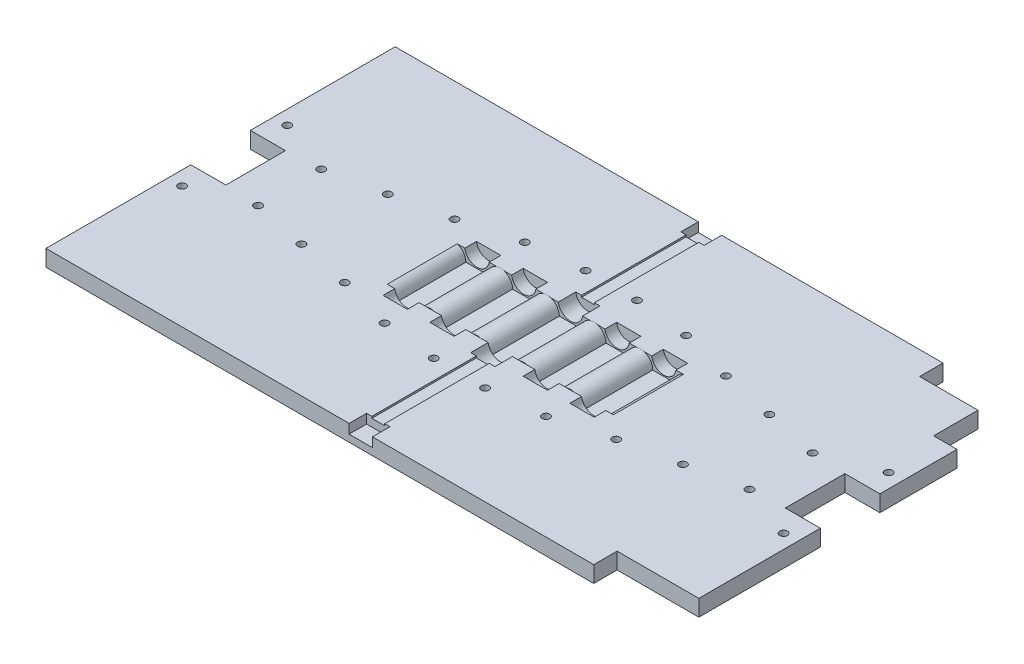
SolidWorks part; units mm, degrees
ref_plane "Front Plane" through (0, 0, 0) normal (0, 0, 1) x (1, 0, 0)
ref_plane "Top Plane" through (0, 0, 0) normal (0, 1, 0) x (1, 0, 0)
ref_plane "Right Plane" through (0, 0, 0) normal (1, 0, 0) x (0, 0, -1)
sketch "Sketch1" plane through (0, 0, 0) normal (0, 1, 0) x (1, 0, 0)
  line L1 (269.5, -149.5) -> (-269.5, -149.5)
  line L2 (269.5, -149.5) -> (269.5, 149.5)
  line L3 (269.5, 149.5) -> (-269.5, 149.5)
  line L4 (-269.5, -149.5) -> (-269.5, 149.5)
  line L5 (269.5, -149.5) -> (-269.5, 149.5) construction
  line L6 (269.5, 149.5) -> (-269.5, -149.5) construction
  point P0 (0, 0)
  dimension "D1" = 299
  dimension "D2" = 539
extrude "Boss-Extrude1" add sketch "Sketch1" against normal blind 14
sketch "Sketch15" plane through (0, 0, 0) normal (0, 1, 0) x (1, 0, 0)
  line L0 (269.5, 149.5) -> (199.5, 149.5)
  line L1 (269.5, 149.5) -> (-269.5, 149.5) construction
  line L2 (199.5, 149.5) -> (199.5, 129.5)
  line L3 (199.5, 129.5) -> (249.5, 129.5)
  line L4 (249.5, 129.5) -> (249.5, 91.5)
  line L5 (249.5, 91.5) -> (269.5, 91.5)
  line L6 (269.5, -149.5) -> (269.5, 149.5) construction
  line L7 (269.5, 91.5) -> (269.5, 149.5)
  line L8 (269.5, -149.5) -> (199.5, -149.5)
  line L9 (-269.5, -149.5) -> (269.5, -149.5) construction
  line L10 (199.5, -149.5) -> (199.5, -129.5)
  line L11 (199.5, -129.5) -> (269.5, -129.5)
  line L12 (269.5, -129.5) -> (269.5, -149.5)
  dimension "D1" = 20
  dimension "D2" = 20
  dimension "D3" = 20
  dimension "D4" = 70
  dimension "D5" = 70
  dimension "D6" = 58
extrude "Cut-Extrude8" cut sketch "Sketch15" against normal through all
sketch "Sketch2" plane through (0, 0, 0) normal (0, 1, 0) x (1, 0, 0)
  line L0 (-269.5, 0) -> (269.5, 0) construction
  line L1 (-269.5, 149.5) -> (-269.5, -149.5) construction
  line L4 (-269.5, -25.5) -> (-239.5, -25.5)
  line L5 (-269.5, -25.5) -> (-269.5, 25.5)
  line L6 (-269.5, 25.5) -> (-239.5, 25.5)
  line L7 (-239.5, -25.5) -> (-239.5, 25.5)
  point P10 (-269.5, 0)
  dimension "D1" = 51
  dimension "D2" = 30
extrude "Cut-Extrude1" cut sketch "Sketch2" against normal through all
mirror "Mirror1" about plane through (0, 0, 0) normal (1, 0, 0) of "Cut-Extrude1"
sketch "Sketch8" plane through (0, -14, 0) normal (0, -1, 0) x (1, 0, 0)
  point P0 (-255, 105)
  point P1 (-170, 105)
  point P5 (-85, 105)
  point P6 (0, 105)
  point P7 (85, 105)
  point P8 (170, 105)
  point P9 (255, 105)
  point P10 (-170, 35)
  point P11 (-85, 35)
  point P12 (0, 35)
  point P13 (85, 35)
  point P14 (170, 35)
  point P15 (255, 35)
  point P16 (-170, -35)
  point P17 (-85, -35)
  point P18 (0, -35)
  point P19 (85, -35)
  point P20 (170, -35)
  point P21 (255, -35)
  point P22 (-170, -105)
  point P23 (-85, -105)
  point P24 (0, -105)
  point P25 (85, -105)
  point P26 (170, -105)
  point P27 (255, -105)
  point P28 (-255, 35)
  point P29 (-255, -35)
  point P30 (-255, -105)
  dimension "D1" = 255
  dimension "D2" = 105
  dimension "D3" = 7
  dimension "D4" = 4
sketch "Sketch16" plane through (0, 0, 0) normal (0, 1, 0) x (1, 0, 0)
  line L1 (100, -30) -> (-100, -30)
  line L2 (100, -30) -> (100, 30)
  line L3 (100, 30) -> (-100, 30)
  line L4 (-100, -30) -> (-100, 30)
  line L5 (100, -30) -> (-100, 30) construction
  line L6 (100, 30) -> (-100, -30) construction
  point P0 (0, 0)
  dimension "D1" = 200
  dimension "D2" = 60
extrude "Cut-Extrude9" cut sketch "Sketch16" against normal blind 10
sketch "Sketch17" plane through (0, 0, -30) normal (0, 0, 1) x (1, 0, 0)
  circle A0 centre (0, 1.5) radius 10.5
  dimension "D1" = 21
  dimension "D2" = 1.5
extrude "Cut-Extrude10" cut sketch "Sketch17" against normal blind 15
sketch "Sketch18" plane through (0, 0, -30) normal (0, 0, 1) x (1, 0, 0)
  line L2 (-79.9719, 1.5) -> (-39.9719, 1.5) construction
  line L3 (-10.3923, 0) -> (-100, 0) construction
  circle A0 centre (-39.9719, 1.5) radius 10.5
  circle A1 centre (-79.9719, 1.5) radius 10.5
  dimension "D1" = 21
  dimension "D2" = 40
  dimension "D3" = 40
  dimension "D4" = 1.5
extrude "Cut-Extrude11" cut sketch "Sketch18" against normal blind 10
sketch "Sketch19" plane through (0, 0, -30) normal (0, 0, 1) x (1, 0, 0)
  line L0 (100, -10) -> (-100, -10) construction
  line L1 (-9.5, -10) -> (-30.5, -10)
  line L3 (-89.5, -10) -> (-100, -10)
  line L4 (-49.5, -10) -> (-70.5, -10)
  line L5 (-100, -10) -> (-100, 0)
  line L6 (-100, 0) -> (-96.7984, 0)
  line L7 (-269.5, 0) -> (199.5, 0) construction
  arc A0 (-49.5, -10) -> (-70.5, -10) centre (-60, -10) ccw
  arc A1 (-9.5, -10) -> (-30.5, -10) centre (-20, -10) ccw
  arc A2 (-89.5, -10) -> (-96.7984, 0) centre (-100, -10) ccw
  dimension "D3" = 21
  dimension "D1" = 40
  dimension "D2" = 40
  dimension "D4" = 20
  dimension "D5" = 10
extrude "Boss-Extrude2" add sketch "Sketch19" along normal up to surface (60 mm away) up to face at (0, -5, 30)
mirror "Mirror2" about plane through (0, 0, 0) normal (1, 0, 0) of "Boss-Extrude2"
mirror "Mirror3" about plane through (0, 0, 0) normal (1, 0, 0) of "Cut-Extrude11"
mirror "Mirror4" about plane through (0, 0, 0) normal (0, 0, 1) of "Cut-Extrude10", "Mirror3", "Cut-Extrude11"
sketch "Sketch20" plane through (0, 0, 0) normal (0, 1, 0) x (1, 0, 0)
  line L0 (-227.025, 3) -> (-227.025, -3)
  line L50 (-90.5, -40) -> (-69.5, -40)
  line L51 (-90.5, -30) -> (-90.5, -40)
  line L52 (-100, -30) -> (-90.5, -30)
  line L53 (-227.025, -3) -> (-100, -30)
  line L54 (-260, -3) -> (-227.025, -3)
  line L55 (-227.025, 3) -> (-260, 3)
  line L56 (-100, 30) -> (-227.025, 3)
  line L57 (-90.5, 30) -> (-100, 30)
  line L58 (-90.5, 40) -> (-90.5, 30)
  line L59 (-69.5, 40) -> (-90.5, 40)
  line L60 (-69.5, 30) -> (-69.5, 40)
  line L61 (-50.5, 30) -> (-69.5, 30)
  line L62 (-50.5, 40) -> (-50.5, 30)
  line L63 (-29.5, 40) -> (-50.5, 40)
  line L64 (-29.5, 30) -> (-29.5, 40)
  line L65 (-10.5, 30) -> (-29.5, 30)
  line L66 (-10.5, 45) -> (-10.5, 30)
  line L67 (10.5, 45) -> (-10.5, 45)
  line L68 (10.5, 30) -> (10.5, 45)
  line L69 (29.5, 30) -> (10.5, 30)
  line L70 (29.5, 40) -> (29.5, 30)
  line L71 (50.5, 40) -> (29.5, 40)
  line L72 (50.5, 30) -> (50.5, 40)
  line L73 (69.5, 30) -> (50.5, 30)
  line L74 (69.5, 40) -> (69.5, 30)
  line L75 (90.5, 40) -> (69.5, 40)
  line L76 (90.5, 30) -> (90.5, 40)
  line L77 (100, 30) -> (90.5, 30)
  line L78 (90.5, -30) -> (100, -30)
  line L79 (260, 3) -> (227.025, 3)
  line L80 (90.5, -30) -> (100, -30)
  line L81 (100, -30) -> (227.025, -3)
  line L82 (100, -30) -> (227.025, -3)
  line L83 (90.5, -40) -> (90.5, -30)
  line L84 (69.5, -40) -> (90.5, -40)
  line L85 (69.5, -30) -> (69.5, -40)
  line L86 (50.5, -30) -> (69.5, -30)
  line L87 (50.5, -40) -> (50.5, -30)
  line L88 (29.5, -40) -> (50.5, -40)
  line L89 (29.5, -30) -> (29.5, -40)
  line L90 (10.5, -30) -> (29.5, -30)
  line L91 (10.5, -45) -> (10.5, -30)
  line L92 (-10.5, -45) -> (10.5, -45)
  line L93 (-10.5, -30) -> (-10.5, -45)
  line L94 (-29.5, -30) -> (-10.5, -30)
  line L95 (-29.5, -40) -> (-29.5, -30)
  line L96 (-50.5, -40) -> (-29.5, -40)
  line L97 (-50.5, -30) -> (-50.5, -40)
  line L98 (-69.5, -30) -> (-50.5, -30)
  line L99 (-69.5, -40) -> (-69.5, -30)
  line L100 (-90.5, -40) -> (-69.5, -40)
  line L101 (-90.5, -30) -> (-90.5, -40)
  line L102 (-100, -30) -> (-90.5, -30)
  line L103 (-227.025, -3) -> (-100, -30)
  line L104 (-260, -3) -> (-227.025, -3)
  line L105 (-227.025, 3) -> (-260, 3)
  line L106 (-100, 30) -> (-227.025, 3)
  line L107 (-90.5, 30) -> (-100, 30)
  line L108 (-90.5, 40) -> (-90.5, 30)
  line L109 (-69.5, 40) -> (-90.5, 40)
  line L110 (-69.5, 30) -> (-69.5, 40)
  line L111 (-50.5, 30) -> (-69.5, 30)
  line L112 (-50.5, 40) -> (-50.5, 30)
  line L113 (-29.5, 40) -> (-50.5, 40)
  line L114 (-29.5, 30) -> (-29.5, 40)
  line L115 (-10.5, 30) -> (-29.5, 30)
  line L116 (-10.5, 45) -> (-10.5, 30)
  line L117 (10.5, 45) -> (-10.5, 45)
  line L118 (10.5, 30) -> (10.5, 45)
  line L119 (29.5, 30) -> (10.5, 30)
  line L120 (29.5, 40) -> (29.5, 30)
  line L121 (50.5, 40) -> (29.5, 40)
  line L122 (50.5, 30) -> (50.5, 40)
  line L123 (69.5, 30) -> (50.5, 30)
  line L124 (69.5, 40) -> (69.5, 30)
  line L125 (90.5, 40) -> (69.5, 40)
  line L126 (90.5, 30) -> (90.5, 40)
  line L127 (100, 30) -> (90.5, 30)
  line L129 (260, 3) -> (227.025, 3)
  line L133 (90.5, -40) -> (90.5, -30)
  line L134 (69.5, -40) -> (90.5, -40)
  line L135 (69.5, -30) -> (69.5, -40)
  line L136 (50.5, -30) -> (69.5, -30)
  line L137 (50.5, -40) -> (50.5, -30)
  line L138 (29.5, -40) -> (50.5, -40)
  line L139 (29.5, -30) -> (29.5, -40)
  line L140 (10.5, -30) -> (29.5, -30)
  line L141 (10.5, -45) -> (10.5, -30)
  line L142 (-10.5, -45) -> (10.5, -45)
  line L143 (-10.5, -30) -> (-10.5, -45)
  line L144 (-29.5, -30) -> (-10.5, -30)
  line L145 (-29.5, -40) -> (-29.5, -30)
  line L146 (-50.5, -40) -> (-29.5, -40)
  line L147 (-50.5, -30) -> (-50.5, -40)
  line L148 (-69.5, -30) -> (-50.5, -30)
  line L149 (-69.5, -40) -> (-69.5, -30)
  line L351 (227.025, -3) -> (260, -3)
  line L352 (227.025, -3) -> (260, -3)
  line L353 (227.025, 3) -> (100, 30)
  line L354 (227.025, 3) -> (100, 30)
  arc A2 (-260, 3) -> (-260, -3) centre (-260, 0) ccw
  arc A3 (260, -3) -> (260, 3) centre (260, 0) ccw
  arc A4 (-260, 3) -> (-260, -3) centre (-260, 0) ccw
  arc A5 (260, -3) -> (260, 3) centre (260, 0) ccw
  dimension "D1" = 0
sketch "Sketch22" plane through (0, 0, 0) normal (0, 1, 0) x (1, 0, 0)
  circle A1 centre (-69.1, -60) radius 2.5
  circle A2 centre (-69.1, -60) radius 2.5
  circle A3 centre (-116.2, -47.0034) radius 2.5
  circle A4 centre (-116.2, -47.0034) radius 2.5
  circle A5 centre (-163.3, -36.992) radius 2.5
  circle A6 centre (-163.3, -36.992) radius 2.5
  circle A7 centre (-210.4, -26.9806) radius 2.5
  circle A8 centre (-210.4, -26.9806) radius 2.5
  circle A9 centre (-257.5, -45) radius 2.5
  circle A10 centre (-257.5, -45) radius 2.5
  circle A11 centre (-22, -65) radius 2.5
  circle A12 centre (-22, -65) radius 2.5
  dimension "D1" = 0
  dimension "D2" = 0
  dimension "D3" = 0
  dimension "D4" = 0
  dimension "D5" = 0
  dimension "D6" = 0
hole_wizard "M6 Clearance Hole1" positions "3DSketch1" profile "Sketch9" hole size "M6" standard "ANSI Metric" end condition through all
sketch3d "3DSketch1"
  point P84 (-257.5, 0, 45)
  point P87 (-210.4, 0, 26.9806)
  point P90 (-163.3, 0, 36.992)
  point P93 (-116.2, 0, 47.0034)
  point P96 (-69.1, 0, 60)
  point P99 (-22, 0, 65)
sketch "Sketch9" plane through (-257.5, 0, 45) normal (1, 0, 0) x (0, 0, 1)
  line L0 (0, 0) -> (0, 14)
  line L1 (0, 14) -> (3.3, 14)
  line L2 (3.3, 14) -> (3.3, 0)
  line L5 (3.3, 0) -> (0, 0)
  line L11 (0, -6.35) -> (0, 107.95) construction
  dimension "Thru Hole Dia." = 6.6
  dimension "Thru Hole Depth" = 14
mirror "Mirror6" about plane through (0, 0, 0) normal (1, 0, 0) of "M6 Clearance Hole1"
mirror "Mirror7" about plane through (0, 0, 0) normal (0, 0, 1) of "Mirror6", "M6 Clearance Hole1"
sketch "Sketch23" plane through (0, 0, 0) normal (0, 1, 0) x (1, 0, 0)
  line L0 (199.5, 149.5) -> (-269.5, 149.5) construction
  line L1 (-5.5, 149.5) -> (5.5, 149.5)
  line L2 (-5.5, 149.5) -> (-5.5, 45)
  line L3 (-5.5, 45) -> (5.5, 45)
  line L4 (5.5, 149.5) -> (5.5, 45)
  line L5 (-10.3923, 45) -> (10.3923, 45) construction
  line L6 (-10.3923, 45) -> (10.3923, 45) construction
  point P10 (0, 45)
  point P11 (0, 45)
  point P12 (0, 45)
  point P13 (6.4064, 45)
  dimension "D1" = 11
extrude "Cut-Extrude12" cut sketch "Sketch23" against normal blind 1.5
sketch "Sketch24" plane through (0, 0, 0) normal (0, 1, 0) x (1, 0, 0)
  line L0 (5.5, 149.5) -> (-5.5, 149.5) construction
  line L1 (10, 164.5) -> (-10, 164.5)
  line L2 (10, 164.5) -> (10, 134.5)
  line L3 (10, 134.5) -> (-10, 134.5)
  line L4 (-10, 164.5) -> (-10, 134.5)
  line L5 (10, 164.5) -> (-10, 134.5) construction
  line L6 (10, 134.5) -> (-10, 164.5) construction
  point P0 (0, 149.5)
  dimension "D1" = 30
  dimension "D2" = 20
extrude "Cut-Extrude13" cut sketch "Sketch24" against normal blind 8
mirror "Mirror8" about plane through (0, 0, 0) normal (0, 0, 1) of "Cut-Extrude13", "Cut-Extrude12"
